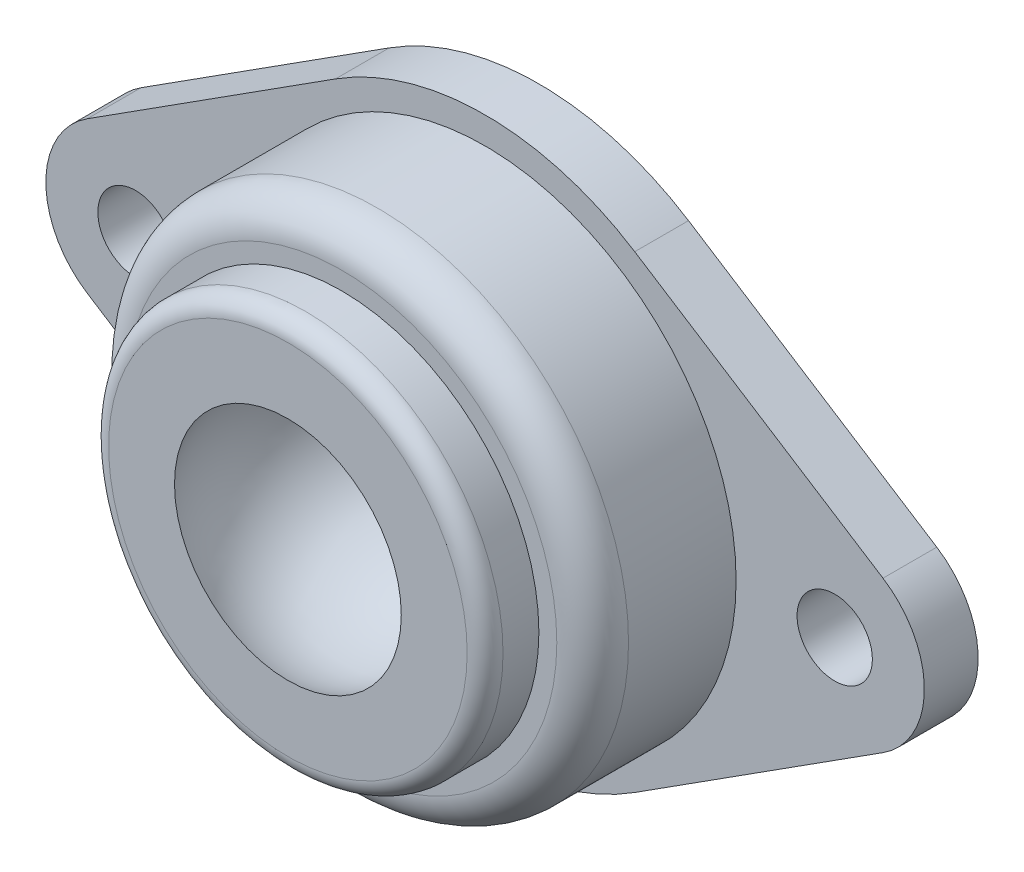
SolidWorks part; units mm, degrees
ref_plane "前视基准面" through (0, 0, 0) normal (0, 0, 1) x (1, 0, 0)
ref_plane "上视基准面" through (0, 0, 0) normal (0, 1, 0) x (1, 0, 0)
ref_plane "右视基准面" through (0, 0, 0) normal (1, 0, 0) x (0, 0, -1)
sketch "草图1" plane through (0, 0, 0) normal (0, 0, 1) x (1, 0, 0)
  line L0 (-19.5, 0) -> (19.5, 0) construction
  line L1 (-22.1923, 4.2133) -> (-8.3462, 13.0611)
  line L2 (-22.1923, -4.2133) -> (-8.3462, -13.0611)
  line L3 (8.3462, 13.0611) -> (22.1923, 4.2133)
  line L4 (8.3462, -13.0611) -> (22.1923, -4.2133)
  circle A0 centre (-19.5, 0) radius 2.1
  circle A1 centre (19.5, 0) radius 2.1
  arc A2 (-22.1923, 4.2133) -> (-22.1923, -4.2133) centre (-19.5, 0) ccw
  arc A3 (22.1923, -4.2133) -> (22.1923, 4.2133) centre (19.5, 0) ccw
  arc A4 (-8.3462, -13.0611) -> (8.3462, -13.0611) centre (0, 0) ccw
  arc A5 (8.3462, 13.0611) -> (-8.3462, 13.0611) centre (0, 0) ccw
  dimension "D1" = 39
  dimension "D2" = 19.5
extrude "凸台-拉伸1" add sketch "草图1" along normal blind 3
sketch "草图2" plane through (0, 0, 3) normal (0, 0, 1) x (1, 0, 0)
  circle A0 centre (0, 0) radius 14
extrude "凸台-拉伸2" add sketch "草图2" along normal blind 8
sketch "草图3" plane through (0, 0, 11) normal (0, 0, 1) x (1, 0, 0)
  circle A0 centre (0, 0) radius 11
extrude "凸台-拉伸3" add sketch "草图3" along normal blind 3
sketch "草图4" plane through (0, 0, 0) normal (1, 0, 0) x (0, 0, -1)
  line L0 (-11, 14) -> (-11, -14) construction
  line L1 (-18, 0) -> (-4, 0)
  arc A0 (-4, 0) -> (-18, 0) centre (-11, 0) ccw
revolve "切除-旋转1" cut sketch "草图4" angle 360 about L1
fillet "圆角1" radius 2 1 edges at (14, 0, 11)
fillet "圆角2" radius 1 1 edges at (11, 0, 14)
